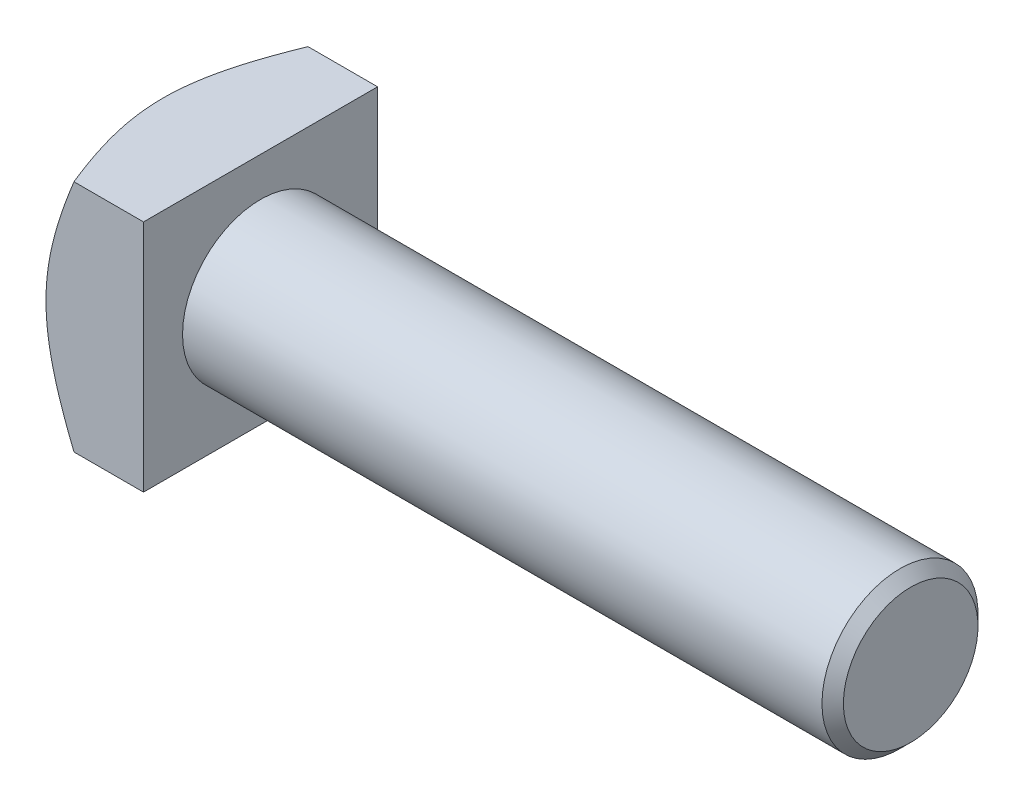
SolidWorks part; units mm, degrees
extrude "BaseHead" add sketch "Sketch1" along normal blind 15
sketch "Sketch1" plane through (0, 0, 0) normal (1, 0, 0) x (0, 0, -1)
  line L0 (18, 18) -> (18, -18)
  line L1 (-18, 18) -> (-18, -18)
  line L2 (0, 0) -> (22.2214, 0) construction
  line L3 (0, 0) -> (0, 20.1834) construction
  line L4 (-18, 18) -> (18, 18)
  line L5 (-18, -18) -> (18, -18)
  dimension "Width_flats" = 36
ref_plane "Plane1" through (0, 0, 0) normal (0, 0, 1) x (1, 0, 0)
ref_plane "Plane2" through (0, 0, 0) normal (0, 1, 0) x (1, 0, 0)
ref_plane "Plane3" through (0, 0, 0) normal (1, 0, 0) x (0, 0, -1)
sketch "BodySke" plane through (0, 0, 0) normal (0, 0, 1) x (1, 0, 0)
  line L0 (0, 18) -> (0, -18) construction
  line L1 (0, 0) -> (115, 0)
  line L2 (0, 0) -> (0, 12)
  line L3 (0, 12) -> (113.352, 12)
  line L4 (115, 0) -> (115, 10.352)
  line L6 (115, 10.352) -> (113.352, 12)
  line L7 (0, 0) -> (96.52, 0) construction
  line L8 (115, -10.352) -> (113.352, -12) construction
  line L9 (0, -12) -> (113.352, -12) construction
  line L10 (18, 15.24) -> (18, -1.27) construction
  line L11 (61, 15.24) -> (61, -1.27) construction
  line L12 (15, 18) -> (15, -18) construction
  line L13 (15, 18) -> (15, -18) construction
  dimension "Length" = 100
  dimension "Diameter" = 24
  dimension "Advance" = 3
revolve "BaseBody" add sketch "BodySke"
cosmetic thread "ThreadCosmetic" [suppressed]
fillet "HeadFillet" [suppressed] radius 0.8
sketch "Sketch3" plane through (0, 0, 0) normal (0, 0, 1) x (1, 0, 0)
  line L0 (0, 18) -> (5.1962, 27)
  line L2 (5.1962, 27) -> (5.1962, 28)
  line L3 (5.1962, 28) -> (-1, 28)
  line L4 (-1, 28) -> (-1, 18)
  line L5 (-1, 18) -> (0, 18)
  line L6 (0, 0) -> (99.06, 0) construction
  line L8 (15, 18) -> (0, 18) construction
  line L9 (0, 18) -> (0, -18) construction
  dimension "D2" = 10
  dimension "D3" = 1
  dimension "D4" = 1
  dimension "Head_ch_ang" = 30
revolve "HeadChamfer" cut sketch "Sketch3" angle 360 about L6
sketch "ThdSchSke" plane through (0, 0, 0) normal (0, 0, 1) x (1, 0, 0)
  line L0 (61, -10.352) -> (59.8461, -12)
  line L1 (61, -10.352) -> (62.1539, -12)
  line L2 (62.1539, -12) -> (62.1539, -15)
  line L3 (-3.175, 0) -> (5.1513, 0) construction
  line L5 (62.1539, -15) -> (59.8461, -15)
  line L6 (59.8461, -15) -> (59.8461, -12)
  dimension "Thread_minor" = 20.704
  dimension "Diameter" = 24
  dimension "Start" = 61
revolve "ThreadSchematic" [suppressed] cut sketch "ThdSchSke" angle 360 about L3
pattern_linear "ThdSchPat" [suppressed]
equation "\"Thread_minor@ThreadCosmetic\" = \"Minor_dia@BodySke\""
equation "\"Thread_length@ThreadCosmetic\" = ((sgn( (\"Length@BodySke\" - \"Advance@BodySke\" * 2 ) - \"Thread_nom@BodySke\" )-1)*( (\"Length@BodySke\" - \"Advance@BodySke\" * 2 ) - \"Thread_nom@BodySke\" ))/-2+ \"Thread_nom@BodySke\""
equation "\"Thread_minor@ThdSchSke\" = \"Minor_dia@BodySke\""
equation "\"Diameter@ThdSchSke\" = \"Diameter@BodySke\""
equation "\"Overcut@ThdSchSke\" = \"Diameter@BodySke\" * 1.25"
equation "\"Start@ThdSchSke\" = \"Head_ht@BaseHead\" + \"Length@BodySke\" - \"Thread_length@ThreadCosmetic\"  '---Non-countersunk---"
equation "\"Num_threads@ThdSchPat\" = int( \"Thread_length@ThreadCosmetic\" / \"Advance@BodySke\" + 0.999 )  + 1"
equation "\"Advance@ThdSchPat\" = \"Thread_length@ThreadCosmetic\" /  (\"Num_threads@ThdSchPat\" - 1) 'relax it"
equation "\"Num_threads@ThdSchPat\" = \"Num_threads@ThdSchPat\" - sgn( \"Num_threads@ThdSchPat\" - 1) '---chamfered tips only---"
